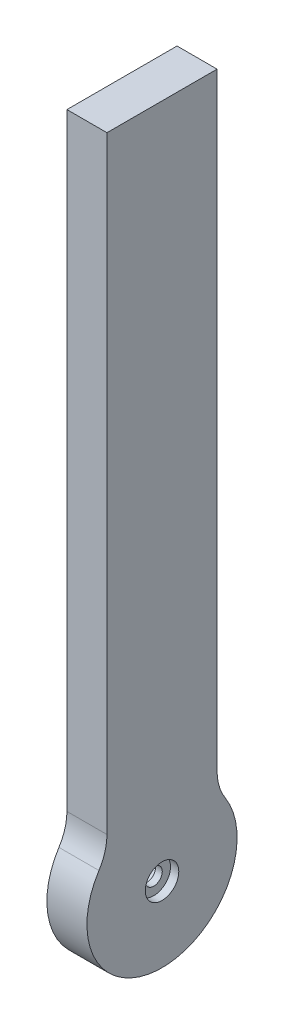
SolidWorks part; units mm, degrees
ref_plane "Front Plane" through (0, 0, 0) normal (0, 0, 1) x (1, 0, 0)
ref_plane "Top Plane" through (0, 0, 0) normal (0, 1, 0) x (1, 0, 0)
ref_plane "Right Plane" through (0, 0, 0) normal (1, 0, 0) x (0, 0, -1)
sketch "Sketch1" plane through (0, 0, 0) normal (1, 0, 0) x (0, 0, -1)
  line L1 (0, 0) -> (44, 0)
  line L2 (0, 0) -> (0, 150)
  line L3 (0, 150) -> (44, 150)
  line L4 (44, 0) -> (44, 150)
  dimension "D1" = 44
  dimension "D2" = 150
extrude "Boss-Extrude1" add sketch "Sketch1" along normal blind 8 contours L3 L4 L1 L2
sketch "Sketch2" plane through (0, 0, 0) normal (1, 0, 0) x (0, 0, -1)
  line L2 (0, 0) -> (44, 0) construction
  line L3 (22, 19) -> (18.5359, 17)
  line L4 (18.5359, 17) -> (18.5359, 13)
  line L5 (18.5359, 13) -> (22, 11)
  line L6 (22, 11) -> (25.4641, 13)
  line L7 (25.4641, 13) -> (25.4641, 17)
  line L8 (25.4641, 17) -> (22, 19)
  circle A0 centre (22, 15) radius 3.4641 construction
  point P1 (0, 0)
  point P11 (22, 0)
  dimension "D1" = 15
  dimension "D2" = 4
extrude "Cut-Extrude3" cut sketch "Sketch2" along normal blind 5
sketch "Sketch3" plane through (8, 0, 0) normal (1, 0, 0) x (0, 0, -1)
  line L0 (11, 150) -> (11, 28.5647)
  line L1 (0, 150) -> (44, 150) construction
  line L2 (22, 150) -> (22, 0) construction
  line L4 (11, 150) -> (33, 150)
  line L5 (18.5359, 15) -> (25.4641, 15) construction
  line L6 (18.5359, 13) -> (18.5359, 17) construction
  line L7 (25.4641, 17) -> (25.4641, 13) construction
  line L8 (33, 150) -> (33, 28.5647)
  line L9 (0, 0) -> (44, 0) construction
  arc A0 (11, 28.5647) -> (9.4, 23.1388) centre (1, 28.5647) cw
  arc A1 (9.4, 23.1388) -> (34.6, 23.1388) centre (22, 15) ccw
  arc A2 (33, 28.5647) -> (34.6, 23.1388) centre (43, 28.5647) ccw
  point P7 (0, 0)
  point P16 (22, 0)
  point P17 (22, 3.2836)
  point P24 (22, 0)
  dimension "D2" = 10
  dimension "D1" = 11
extrude "Cut-Extrude4" cut sketch "Sketch3" against normal up to next (8 mm away) flip side to cut
hole_wizard "CBORE for M3 SBHCS1" positions "Sketch5" profile "Sketch6" counterbore size "M3" standard "ANSI Metric" end condition up to next
sketch "Sketch5" plane through (8, 0, 0) normal (1, 0, 0) x (0, 0, -1)
  arc A0 (9.4, 23.1388) -> (34.6, 23.1388) centre (22, 15) ccw construction
  point P0 (22, 15)
sketch "Sketch6" plane through (8, 15, -22) normal (0, 1, 0) x (0, 0, -1)
  line L0 (0, 0) -> (0, 3)
  line L1 (0, 3) -> (1.7, 3)
  line L3 (1.7, 3) -> (1.7, 1.65)
  line L4 (1.7, 1.65) -> (3.35, 1.65)
  line L5 (3.35, 1.65) -> (3.35, 0)
  line L7 (3.35, 0) -> (0, 0)
  line L11 (0, -6.35) -> (0, 107.95) construction
  dimension "Thru Hole Dia." = 3.4
  dimension "Thru Hole Depth" = 3
  dimension "C'Bore Dia." = 6.7
  dimension "C'Bore Depth" = 1.65
